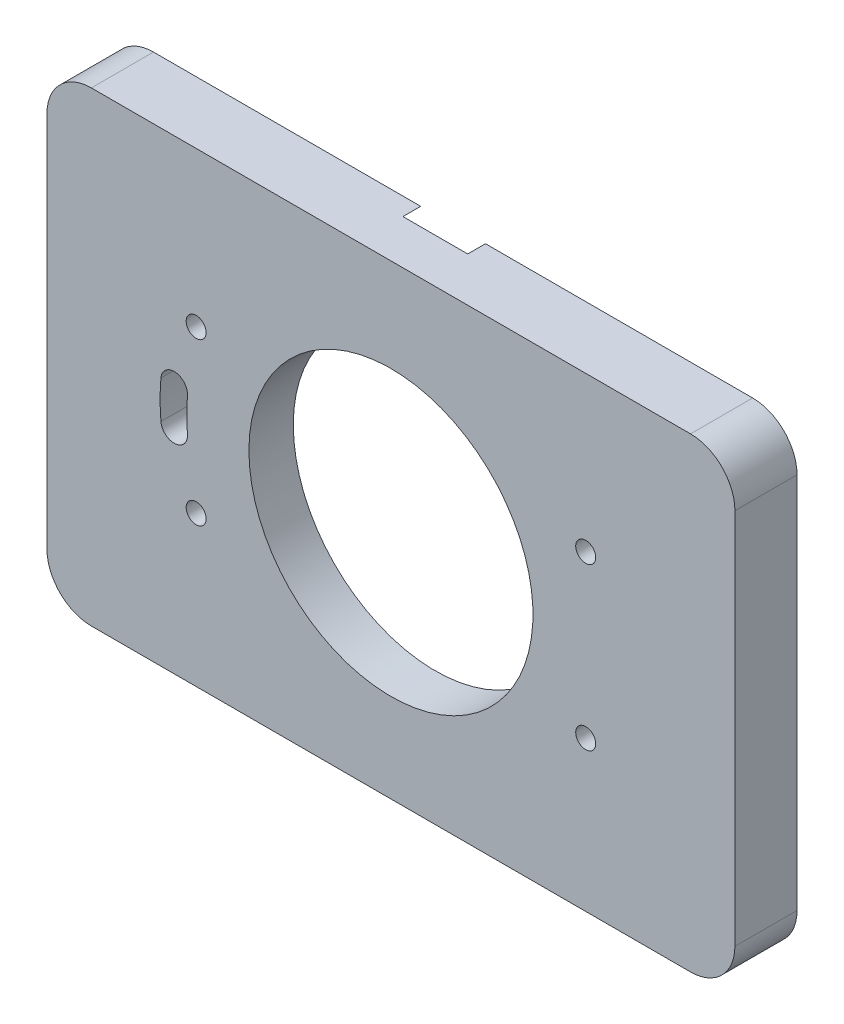
SolidWorks part; units mm, degrees
material "Oak"
ref_plane "Front Plane" through (0, 0, 0) normal (0, 0, 1) x (1, 0, 0)
ref_plane "Top Plane" through (0, 0, 0) normal (0, 1, 0) x (1, 0, 0)
ref_plane "Right Plane" through (0, 0, 0) normal (1, 0, 0) x (0, 0, -1)
sketch "Sketch2" plane through (0, 0, 0) normal (0, 0, 1) x (1, 0, 0)
  line L1 (-77.5, 52.5) -> (77.5, 52.5)
  line L2 (-77.5, 52.5) -> (-77.5, -52.5)
  line L3 (-77.5, -52.5) -> (77.5, -52.5)
  line L4 (77.5, 52.5) -> (77.5, -52.5)
  line L5 (-77.5, 52.5) -> (77.5, -52.5) construction
  line L6 (-77.5, -52.5) -> (77.5, 52.5) construction
  point P0 (0, 0)
  dimension "D1" = 105
  dimension "D2" = 155
extrude "Boss-Extrude1" add sketch "Sketch2" along normal blind 14
sketch "Sketch3" plane through (0, 0, 0) normal (0, 0, -1) x (-1, 0, 0)
  line L0 (-77.5, 52.5) -> (77.5, 52.5) construction
  circle A1 centre (0, -0.5) radius 53.5
  dimension "D1" = 107
  dimension "D2" = 53
extrude "Cut-Extrude1" cut sketch "Sketch3" against normal blind 4
sketch "Sketch4" plane through (0, 0, 4) normal (0, 0, -1) x (-1, 0, 0)
  circle A0 centre (0, -0.5) radius 32
  dimension "D1" = 64
extrude "Cut-Extrude2" cut sketch "Sketch4" against normal blind 10
fillet "Fillet1" radius 10 4 edges at (77.5, -52.5, 7) (77.5, 52.5, 7) (-77.5, -52.5, 7) (-77.5, 52.5, 7)
sketch "Sketch5" plane through (0, 0, 14) normal (0, 0, 1) x (1, 0, 0)
  line L0 (0, -0.5) -> (-25.9373, -0.5) construction
  line L1 (0, -0.5) -> (-43.8843, 17.6775) construction
  line L2 (0, -0.5) -> (-43.8843, -18.6775) construction
  circle A0 centre (43.8843, 17.6775) radius 2.25
  circle A1 centre (43.8843, -18.6775) radius 2.25
  circle A2 centre (-43.8843, -18.6775) radius 2.25
  circle A3 centre (-43.8843, 17.6775) radius 2.25
  circle A5 centre (0, -0.5) radius 47.5 construction
  dimension "D1" = 4.5
  dimension "D2" = 95
  dimension "D3" = 22.5
  dimension "D4" = 45
extrude "Cut-Extrude3" cut sketch "Sketch5" against normal through all
sketch "Sketch6" plane through (0, 0, 0) normal (0, 0, -1) x (-1, 0, 0)
  circle A0 centre (0, -0.5) radius 46 construction
  arc A1 (45.8465, -4.2551) -> (45.8465, 3.2551) centre (0, -0.5) ccw
  arc A2 (48.8365, 6.5) -> (45.8465, 3.2551) centre (48.8365, 3.5) ccw construction
  arc A3 (45.8465, -4.2551) -> (48.8365, -7.5) centre (48.8365, -4.5) ccw construction
  arc A6 (51.8264, 3.7449) -> (45.8465, 3.2551) centre (48.8365, 3.5) ccw
  arc A7 (45.8465, -4.2551) -> (51.8264, -4.7449) centre (48.8365, -4.5) ccw
  arc A8 (51.8264, -4.7449) -> (51.8264, 3.7449) centre (0, -0.5) ccw
extrude "Cut-Extrude4" cut sketch "Sketch6" against normal through all
sketch "Sketch7" [suppressed] plane through (0, 0, 10) normal (0, 0, 1) x (1, 0, 0)
  circle A0 centre (-62, 17.2232) radius 2.75
  circle A1 centre (-62, -12.7768) radius 2.75
  circle A2 centre (68, 17.2232) radius 2.75
  circle A3 centre (68, -12.7768) radius 2.75
  dimension "D1" = 5.5
extrude "Cut-Extrude5" [suppressed] cut sketch "Sketch7" against normal blind 10
sketch "Sketch8" plane through (0, 0, 4) normal (0, 0, -1) x (-1, 0, 0)
  circle A0 centre (43.8843, 17.6775) radius 5
  circle A1 centre (43.8843, -18.6775) radius 5
  circle A2 centre (-43.8843, 17.6775) radius 5
  circle A3 centre (-43.8843, -18.6775) radius 5
  dimension "D1" = 10
extrude "Cut-Extrude6" cut sketch "Sketch8" against normal blind 2.5
